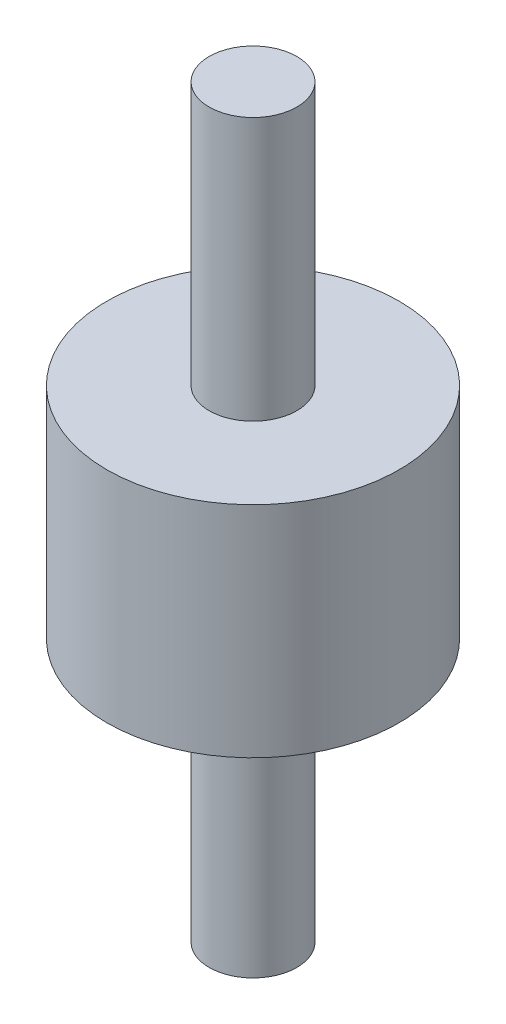
SolidWorks part; units mm, degrees
ref_plane "Front Plane" through (0, 0, 0) normal (0, 0, 1) x (1, 0, 0)
ref_plane "Top Plane" through (0, 0, 0) normal (0, 1, 0) x (1, 0, 0)
ref_plane "Right Plane" through (0, 0, 0) normal (1, 0, 0) x (0, 0, -1)
sketch "Sketch1" plane through (0, 0, 0) normal (0, 0, 1) x (1, 0, 0)
  line L0 (0, 51) -> (-3, 51)
  line L1 (-3, 51) -> (-3, 33)
  line L2 (-3, 33) -> (-10, 33)
  line L3 (-10, 33) -> (-10, 18)
  line L4 (-10, 18) -> (-3, 18)
  line L5 (-3, 18) -> (-3, 0)
  line L6 (-3, 0) -> (0, 0)
  line L7 (0, 0) -> (0, 51)
  dimension "D1" = 3
  dimension "D2" = 18
  dimension "D3" = 18
  dimension "D4" = 15
  dimension "D5" = 10
revolve "Revolve1" add sketch "Sketch1" angle 360 about L7
